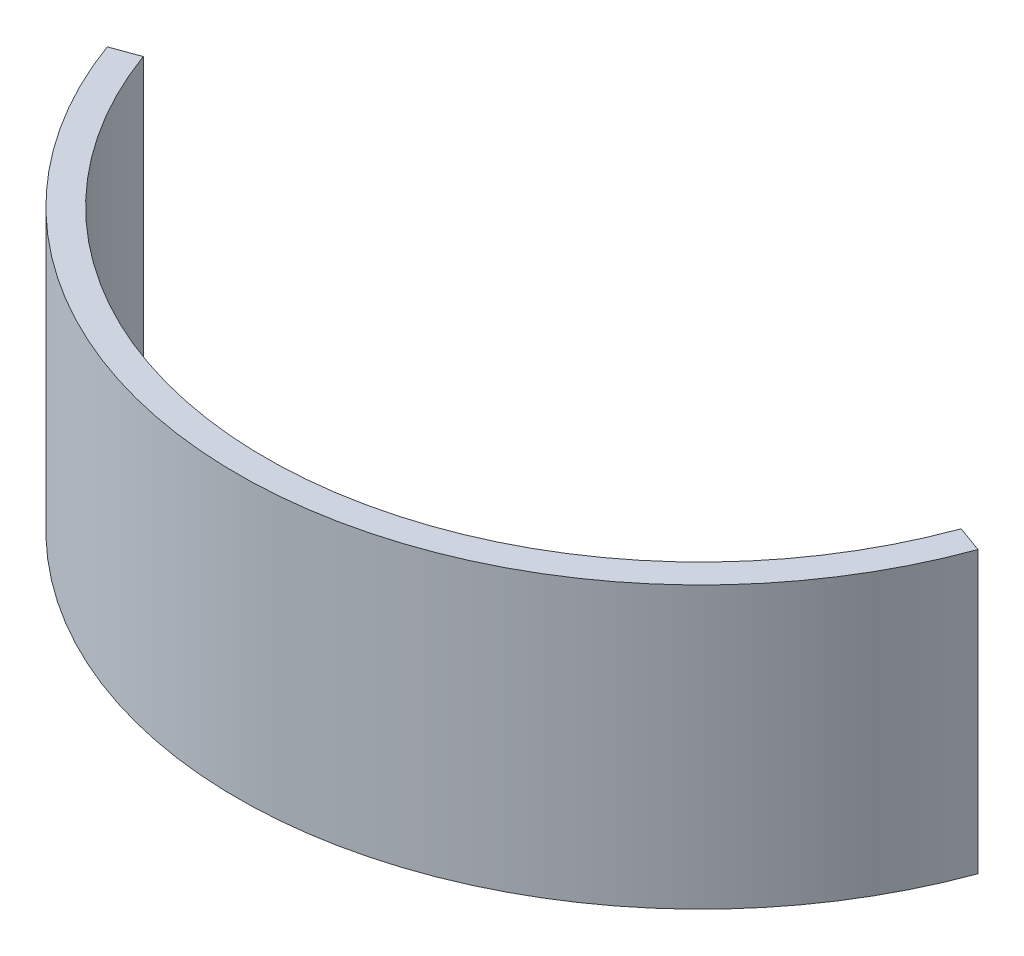
SolidWorks part; units mm, degrees
ref_plane "Front" through (0, 0, 0) normal (0, 0, 1) x (1, 0, 0)
ref_plane "Top" through (0, 0, 0) normal (0, 1, 0) x (1, 0, 0)
ref_plane "Right" through (0, 0, 0) normal (1, 0, 0) x (0, 0, -1)
sketch "Sketch1" plane through (0, 0, 0) normal (0, 1, 0) x (1, 0, 0)
  line L0 (0, 0) -> (-47.3431, -17.2315) construction
  line L1 (0, 0) -> (0, -52.1404) construction
  line L2 (0, 0) -> (47.3431, -17.2315) construction
  arc A0 (-31.0099, -11.2867) -> (31.0099, -11.2867) centre (0, 0) ccw
  dimension "D1" = 66
  dimension "D2" = 70
extrude "Extrude-Thin1" add sketch "Sketch1" along normal blind 20 thin thin type one direction reverse wall 2
